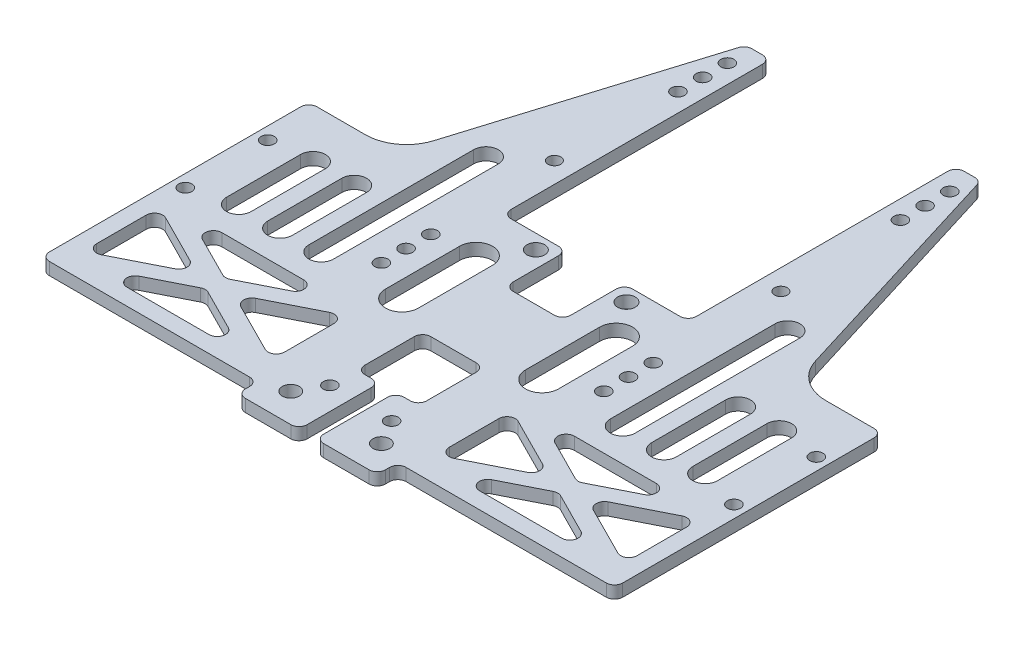
SolidWorks part; units mm, degrees
material "Thornel Mat VMA"
ref_plane "前视基准面" through (0, 0, 0) normal (0, 0, 1) x (1, 0, 0)
ref_plane "上视基准面" through (0, 0, 0) normal (0, 1, 0) x (1, 0, 0)
ref_plane "右视基准面" through (0, 0, 0) normal (1, 0, 0) x (0, 0, -1)
other "Configuration Table"
sketch "草图1" plane through (0, 0, 0) normal (0, 1, 0) x (1, 0, 0)
  line L1 (-69.6, 32.5) -> (69.6, 32.5)
  line L2 (-69.6, 32.5) -> (-69.6, -32.5)
  line L3 (-69.6, -32.5) -> (69.6, -32.5)
  line L4 (69.6, 32.5) -> (69.6, -32.5)
  line L5 (-69.6, 32.5) -> (69.6, -32.5) construction
  line L6 (-69.6, -32.5) -> (69.6, 32.5) construction
  point P0 (0, 0)
  dimension "D1" = 139.2
  dimension "D2" = 65
extrude "凸台-拉伸1" add sketch "草图1" along normal blind 3
sketch "草图2" plane through (0, 3, 0) normal (0, 1, 0) x (1, 0, 0)
  line L0 (-7.5, -24.5) -> (7.5, -24.5) construction
  line L1 (-69.6, -32.5) -> (69.6, -32.5) construction
  circle A0 centre (-7.5, -24.5) radius 1.6
  circle A1 centre (7.5, -24.5) radius 1.6
  point P4 (0, -24.5)
  dimension "D1" = 3.2
  dimension "D2" = 8
  dimension "D3" = 15
extrude "切除-拉伸1" cut sketch "草图2" against normal blind 3
sketch "草图5" plane through (0, 0, 0) normal (0, -1, 0) x (1, 0, 0)
  line L0 (69.6, -32.5) -> (-69.6, -32.5) construction
  line L1 (-22.5, -32.5) -> (-28.5, -32.5)
  line L2 (-22.5, -32.5) -> (-22.5, -97.5)
  line L3 (-22.5, -97.5) -> (-28.5, -97.5)
  line L4 (-28.5, -32.5) -> (-28.5, -97.5)
  line L5 (-22.5, -32.5) -> (22.5, -32.5) construction
  line L6 (22.5, -32.5) -> (28.5, -32.5)
  line L7 (22.5, -32.5) -> (22.5, -97.5)
  line L8 (22.5, -97.5) -> (28.5, -97.5)
  line L9 (28.5, -32.5) -> (28.5, -97.5)
  line L10 (28.5, -97.5) -> (48.5, -32.5)
  line L11 (48.5, -32.5) -> (28.5, -32.5)
  line L12 (-28.5, -97.5) -> (-48.5, -32.5)
  line L13 (-48.5, -32.5) -> (-28.5, -32.5)
  point P10 (0, -32.5)
  line M17 (-69.6, -32.5) -> (69.6, -32.5)
  dimension "D1" = 6
  dimension "D2" = 65
  dimension "D3" = 20
  dimension "D4" = 45
extrude "凸台-拉伸2" add sketch "草图5" against normal blind 3 contours L12 L4 M17 | L4 L3 L2 M17 | L9 L7 L8 M17 | L9 L10 M17
sketch "草图6" plane through (0, 3, 0) normal (0, 1, 0) x (1, 0, 0)
  line L0 (22.5, 32.5) -> (-22.5, 32.5) construction
  line L1 (-7, 32.5) -> (7, 32.5)
  line L2 (-7, 32.5) -> (-7, 17.5)
  line L3 (-7, 17.5) -> (7, 17.5)
  line L4 (7, 32.5) -> (7, 17.5)
  circle A0 centre (11, 29) radius 2.15
  circle A1 centre (-11, 29) radius 2.15
  point P12 (0, 17.5)
  dimension "D1" = 4.3
  dimension "D2" = 14
  dimension "D3" = 15
extrude "切除-拉伸2" cut sketch "草图6" against normal blind 3
sketch "草图7" plane through (0, 3, 0) normal (0, 1, 0) x (1, 0, 0)
  line L0 (22.5, 97.5) -> (28.5, 97.5) construction
  line L1 (-27, 91.5) -> (27, 91.5) construction
  line L2 (-27, 91.5) -> (-27, 19.5) construction
  line L3 (-27, 19.5) -> (27, 19.5) construction
  line L4 (27, 91.5) -> (27, 19.5) construction
  line L5 (-27, 91.5) -> (27, 19.5) construction
  line L6 (-27, 19.5) -> (27, 91.5) construction
  circle A0 centre (27, 91.5) radius 1.6
  circle A1 centre (-27, 91.5) radius 1.6
  circle A2 centre (-27, 19.5) radius 1.6
  circle A3 centre (27, 19.5) radius 1.6
  point P0 (0, 55.5)
  dimension "D3" = 3.2
  dimension "D1" = 54
  dimension "D2" = 72
  dimension "D4" = 6
extrude "切除-拉伸3" cut sketch "草图7" against normal blind 10
pattern_linear "阵列(线性)1" count 3 spacing 6 along (0, 0, 1) of "切除-拉伸3"
fillet "圆角1" radius 10 2 edges at (48.5, 1.5, -32.5) (-48.5, 1.5, -32.5)
fillet "圆角2" radius 2 14 edges at (-7, 1.5, -17.5) (7, 1.5, -17.5) (7, 1.5, -32.5) (22.5, 1.5, -32.5) (22.5, 1.5, -97.5) (28.5, 1.5, -97.5) (69.6, 1.5, -32.5) (69.6, 1.5, 32.5) (-69.6, 1.5, 32.5) (-28.5, 1.5, -97.5) (-22.5, 1.5, -97.5) (-22.5, 1.5, -32.5) (-7, 1.5, -32.5) (-69.6, 1.5, -32.5)
sketch "草图8" plane through (0, 3, 0) normal (0, 1, 0) x (1, 0, 0)
  line L0 (0, -39.2888) -> (0, 37.2382) construction
  line L6 (-7.5, -2) -> (7.5, -2)
  line L7 (-7.5, -2) -> (-7.5, -18)
  line L8 (-7.5, -18) -> (7.5, -18)
  line L9 (7.5, -2) -> (7.5, -18)
  circle A0 centre (66.6, 19.5) radius 1.6
  circle A1 centre (66.6, -0.5) radius 1.6
  circle A2 centre (-66.6, -0.5) radius 1.6
  circle A3 centre (-66.6, 19.5) radius 1.6
  point P18 (0, -2)
  dimension "D1" = 3.2
  dimension "D2" = 15
  dimension "D3" = 16
  dimension "D4" = 2
extrude "切除-拉伸4" cut sketch "草图8" against normal blind 10
sketch "草图9" plane through (0, 3, 0) normal (0, 1, 0) x (1, 0, 0)
  line L0 (-7.5, -18) -> (7.5, -18) construction
  line L1 (-2, -18) -> (2, -18)
  line L2 (-2, -18) -> (-2, -32.5)
  line L3 (-2, -32.5) -> (2, -32.5)
  line L4 (2, -18) -> (2, -32.5)
  line L5 (-67.6, -32.5) -> (67.6, -32.5) construction
  line L6 (-56.6, 20.5) -> (-56.6, 2.5) construction
  line L7 (-53.6, 20.5) -> (-53.6, 2.5)
  line L8 (-59.6, 20.5) -> (-59.6, 2.5)
  line L9 (-69.6, 30.5) -> (-69.6, -30.5) construction
  line L10 (-65.6, -5.5) -> (-20, -5.5)
  line L11 (-65.6, -5.5) -> (-65.6, -28.5)
  line L12 (-65.6, -28.5) -> (-20, -28.5)
  line L13 (-20, -5.5) -> (-20, -28.5)
  line L14 (-55.8857, 32.5) -> (-67.6, 32.5) construction
  line L15 (0, -57.0981) -> (0, 23.5766) construction
  line L16 (56.6, 20.5) -> (56.6, 2.5) construction
  line L17 (53.6, 20.5) -> (53.6, 2.5)
  line L18 (59.6, 20.5) -> (59.6, 2.5)
  line L19 (65.6, -28.5) -> (20, -28.5)
  line L20 (20, -5.5) -> (20, -28.5)
  line L21 (65.6, -5.5) -> (65.6, -28.5)
  line L22 (65.6, -5.5) -> (20, -5.5)
  line L23 (-46.6, 20.5) -> (-46.6, 2.5) construction
  line L24 (-43.6, 20.5) -> (-43.6, 2.5)
  line L25 (-49.6, 20.5) -> (-49.6, 2.5)
  line L26 (-36.6, 42.5) -> (-36.6, 2.5) construction
  line L27 (-33.6, 42.5) -> (-33.6, 2.5)
  line L28 (-39.6, 42.5) -> (-39.6, 2.5)
  line L29 (-17, 20.5) -> (-17, 2.5) construction
  line L30 (-13, 20.5) -> (-13, 2.5)
  line L31 (-21, 20.5) -> (-21, 2.5)
  line L32 (17, 20.5) -> (17, 2.5) construction
  line L33 (13, 20.5) -> (13, 2.5)
  line L34 (21, 20.5) -> (21, 2.5)
  line L35 (36.6, 42.5) -> (36.6, 2.5) construction
  line L36 (33.6, 42.5) -> (33.6, 2.5)
  line L37 (39.6, 42.5) -> (39.6, 2.5)
  line L38 (46.6, 20.5) -> (46.6, 2.5) construction
  line L39 (43.6, 20.5) -> (43.6, 2.5)
  line L40 (49.6, 20.5) -> (49.6, 2.5)
  arc A0 (-53.6, 20.5) -> (-59.6, 20.5) centre (-56.6, 20.5) ccw
  arc A1 (-59.6, 2.5) -> (-53.6, 2.5) centre (-56.6, 2.5) ccw
  arc A2 (53.6, 20.5) -> (59.6, 20.5) centre (56.6, 20.5) cw
  arc A3 (59.6, 2.5) -> (53.6, 2.5) centre (56.6, 2.5) cw
  arc A4 (-43.6, 20.5) -> (-49.6, 20.5) centre (-46.6, 20.5) ccw
  arc A5 (-49.6, 2.5) -> (-43.6, 2.5) centre (-46.6, 2.5) ccw
  arc A6 (-33.6, 42.5) -> (-39.6, 42.5) centre (-36.6, 42.5) ccw
  arc A7 (-39.6, 2.5) -> (-33.6, 2.5) centre (-36.6, 2.5) ccw
  arc A8 (-13, 20.5) -> (-21, 20.5) centre (-17, 20.5) ccw
  arc A9 (-21, 2.5) -> (-13, 2.5) centre (-17, 2.5) ccw
  arc A10 (13, 20.5) -> (21, 20.5) centre (17, 20.5) cw
  arc A11 (21, 2.5) -> (13, 2.5) centre (17, 2.5) cw
  arc A12 (33.6, 42.5) -> (39.6, 42.5) centre (36.6, 42.5) cw
  arc A13 (39.6, 2.5) -> (33.6, 2.5) centre (36.6, 2.5) cw
  arc A14 (43.6, 20.5) -> (49.6, 20.5) centre (46.6, 20.5) cw
  arc A15 (49.6, 2.5) -> (43.6, 2.5) centre (46.6, 2.5) cw
  point P8 (0, -18)
  point P12 (-56.6, 11.5)
  point P29 (56.6, 11.5)
  point P41 (-46.6, 11.5)
  point P47 (-36.6, 22.5)
  point P52 (-17, 11.5)
  point P63 (17, 11.5)
  point P70 (36.6, 22.5)
  point P77 (46.6, 11.5)
  dimension "D6" = 3
  dimension "D14" = 4
  dimension "D1" = 4
  dimension "D2" = 4
  dimension "D3" = 4
  dimension "D4" = 13
  dimension "D5" = 18
  dimension "D7" = 12
  dimension "D8" = 23
  dimension "D9" = 20
  dimension "D11" = 4
  dimension "D12" = 4
  dimension "D13" = 40
  dimension "D15" = 21
  dimension "D10" = 2
extrude "切除-拉伸5" cut sketch "草图9" against normal blind 10
sketch "草图10" plane through (0, 3, 0) normal (0, 1, 0) x (1, 0, 0)
  line L0 (-20, -5.5) -> (-65.6, -28.5)
  line L1 (-65.6, -5.5) -> (-20, -28.5)
  line L2 (20, -5.5) -> (65.6, -28.5)
  line L3 (20, -28.5) -> (65.6, -5.5)
  line L4 (20, -5.5) -> (20, -28.5) construction
  line L5 (20, -28.5) -> (65.6, -28.5) construction
extrude "拉伸-薄壁1" add sketch "草图10" against normal blind 3 thin thin type mid plane wall 4
fillet "圆角3" radius 2 32 edges at (-42.8, 1.5, 14.76) (-61.1589, 1.5, 5.5) (-24.4411, 1.5, 5.5) (-20, 1.5, 26.26) (-38.3589, 1.5, 17) (-20, 1.5, 7.74) (-47.2411, 1.5, 17) (-65.6, 1.5, 26.26) (-42.8, 1.5, 19.24) (-24.4411, 1.5, 28.5) (-61.1589, 1.5, 28.5) (-7.5, 1.5, 18) (-7.5, 1.5, 2) (7.5, 1.5, 2) (7.5, 1.5, 18) (2, 1.5, 18) (2, 1.5, 32.5) (-2, 1.5, 32.5) (-2, 1.5, 18) (47.2411, 1.5, 17) (65.6, 1.5, 7.74) (65.6, 1.5, 26.26) (24.4411, 1.5, 28.5) (42.8, 1.5, 19.24) (61.1589, 1.5, 28.5) (61.1589, 1.5, 5.5) (42.8, 1.5, 14.76) (24.4411, 1.5, 5.5) (38.3589, 1.5, 17) (20, 1.5, 26.26) (20, 1.5, 7.74) (-65.6, 1.5, 7.74)
sketch "草图11" plane through (0, 3, 0) normal (0, 1, 0) x (1, 0, 0)
  line L0 (0, -18.9649) -> (0, 0) construction
  line L1 (2, -30.5) -> (17, -30.5)
  line L2 (2, -30.5) -> (2, -37.5)
  line L3 (2, -37.5) -> (17, -37.5)
  line L4 (17, -30.5) -> (17, -37.5)
  line L5 (4, -32.5) -> (67.6, -32.5) construction
  line L6 (-17, -30.5) -> (-17, -37.5)
  line L7 (-2, -37.5) -> (-17, -37.5)
  line L8 (-2, -30.5) -> (-2, -37.5)
  line L9 (-2, -30.5) -> (-17, -30.5)
  dimension "D1" = 5
  dimension "D2" = 15
extrude "凸台-拉伸3" add sketch "草图11" against normal blind 3
fillet "圆角4" radius 2 6 edges at (2, 1.5, 37.5) (17, 1.5, 32.5) (-17, 1.5, 32.5) (-17, 1.5, 37.5) (-2, 1.5, 37.5) (17, 1.5, 37.5)
sketch "草图12" plane through (0, 3, 0) normal (0, 1, 0) x (1, 0, 0)
  circle A0 centre (-11, -30.5) radius 2.05
  circle A1 centre (11, -30.5) radius 2.05
  dimension "D1" = 4.1
extrude "切除-拉伸6" cut sketch "草图12" against normal blind 3
sketch "草图13" plane through (0, 3, 0) normal (0, 1, 0) x (1, 0, 0)
  line L0 (-27.5, 50) -> (27.5, 50) construction
  circle A0 centre (27.5, 50) radius 1.55
  circle A1 centre (-27.5, 50) radius 1.55
  point P4 (0, 50)
  dimension "D1" = 3.1
  dimension "D2" = 55
  dimension "D3" = 50
extrude "切除-拉伸7" cut sketch "草图13" against normal blind 10
